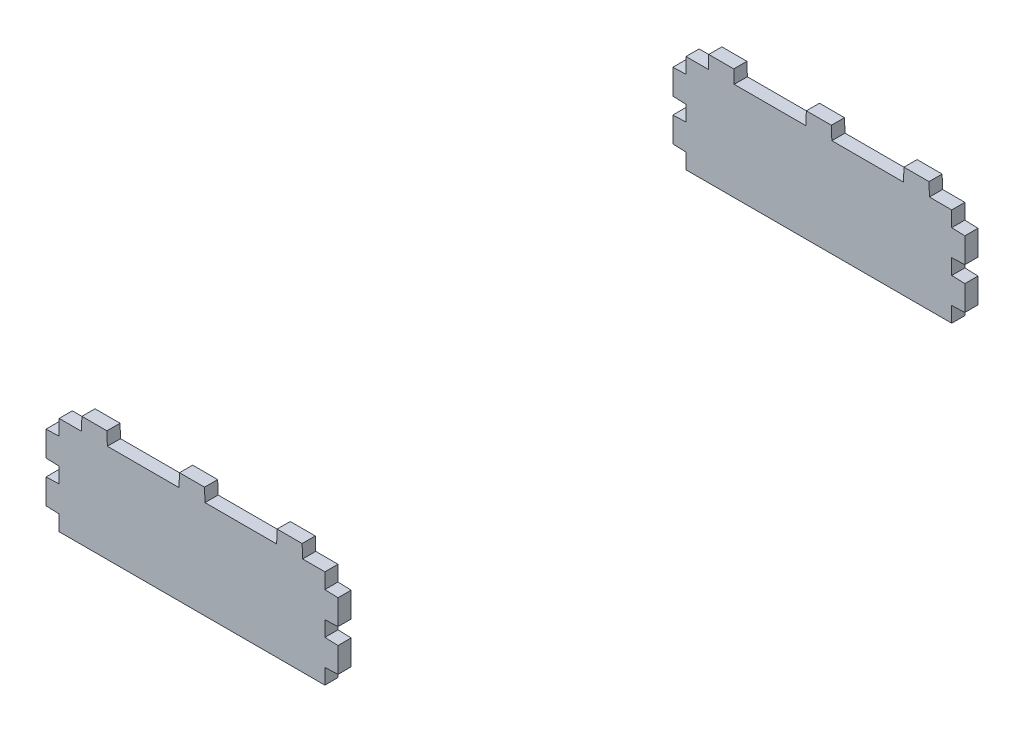
SolidWorks part; units mm, degrees
ref_plane "Front Plane" through (0, 0, 0) normal (0, 0, 1) x (1, 0, 0)
ref_plane "Top Plane" through (0, 0, 0) normal (0, 1, 0) x (1, 0, 0)
ref_plane "Right Plane" through (0, 0, 0) normal (1, 0, 0) x (0, 0, -1)
sketch "Sketch1" plane through (0, 0, -76.2) normal (0, 0, -1) x (-1, 0, 0)
  line L0 (-60.6368, 0) -> (-66.6368, 0) construction
  line L1 (-72.9868, 44.8) -> (-50.2673, 44.8) construction
  line L2 (-60.6368, 0) -> (-66.6368, 0) construction
  line L3 (-72.9868, 44.8) -> (-50.2673, 44.8) construction
  line L4 (60.6368, 0) -> (60.6368, 7.2435) construction
  line L5 (-60.6368, 0) -> (-60.6368, 7.2435) construction
  line L6 (60.6368, 0) -> (60.6368, 7.2435) construction
  line L7 (-60.6368, 0) -> (-60.6368, 7.2435) construction
  line L9 (-50.4768, 44.8) -> (-50.2673, 50.8)
  line L10 (-72.9868, 50.8) -> (-50.2673, 50.8) construction
  line L11 (-50.2673, 50.8) -> (-38.8373, 50.8)
  line L12 (-38.8373, 50.8) -> (-38.6278, 44.8)
  line L13 (-38.6278, 44.8) -> (-5.9245, 44.8)
  line L14 (-5.9245, 44.8) -> (-5.715, 50.8)
  line L15 (-5.715, 50.8) -> (5.715, 50.8)
  line L16 (5.715, 50.8) -> (5.9245, 44.8)
  line L17 (5.9245, 44.8) -> (38.6278, 44.8)
  line L18 (38.6278, 44.8) -> (38.8373, 50.8)
  line L19 (38.8373, 50.8) -> (50.2673, 50.8)
  line L20 (50.2673, 50.8) -> (50.4768, 44.8)
  line L23 (-60.6368, 37.766) -> (-66.6368, 37.5565)
  line L24 (-66.6368, 0) -> (-66.6368, 7.2435) construction
  line L25 (-66.6368, 37.5565) -> (-66.6368, 26.1265)
  line L26 (-66.6368, 26.1265) -> (-60.6368, 25.917)
  line L27 (-60.6368, 25.917) -> (-60.6368, 18.883)
  line L28 (-60.6368, 18.883) -> (-66.6368, 18.6735)
  line L29 (-66.6368, 18.6735) -> (-66.6368, 7.2435)
  line L30 (-66.6368, 7.2435) -> (-60.6368, 7.034)
  line L31 (-60.6368, 7.034) -> (-60.6368, 0)
  line L32 (0, -949.2) -> (0, 49050.8) construction
  line L34 (60.6368, 37.766) -> (66.6368, 37.5565)
  line L35 (66.6368, 37.5565) -> (66.6368, 26.1265)
  line L36 (66.6368, 26.1265) -> (60.6368, 25.917)
  line L37 (60.6368, 25.917) -> (60.6368, 18.883)
  line L38 (60.6368, 18.883) -> (66.6368, 18.6735)
  line L39 (66.6368, 18.6735) -> (66.6368, 7.2435)
  line L40 (66.6368, 7.2435) -> (60.6368, 7.034)
  line L41 (60.6368, 7.034) -> (60.6368, 0)
  line L42 (-60.6368, 0) -> (60.6368, 0)
  line L43 (-50.4768, 44.8) -> (-60.6368, 44.8)
  line L44 (-60.6368, 44.8) -> (-60.6368, 37.766)
  line L45 (-60.6368, 37.5565) -> (-60.6368, 44.8) construction
  line L46 (50.4768, 44.8) -> (60.6368, 44.8)
  line L47 (50.2673, 44.8) -> (72.9868, 44.8) construction
  line L48 (60.6368, 44.8) -> (60.6368, 37.766)
  line L49 (60.6368, 37.5565) -> (60.6368, 44.8) construction
  point P37 (0, 50.8)
  point P43 (0, 0)
  point P51 (-48.562, 50.8)
  point P52 (-48.2607, 44.8)
  dimension "D1" = 11.43
  dimension "D2" = 88
  dimension "D3" = 10.16
  dimension "D4" = 92
  dimension "D5" = 11.43
extrude "Boss-Extrude1" add sketch "Sketch1" against normal blind 6
ref_plane "Plane1" through (0, 0, 69.85) normal (0, 0, -1) x (-1, 0, 0)
mirror "Mirror1" about plane through (0, 0, 69.85) normal (0, 0, -1) of bodies 101
